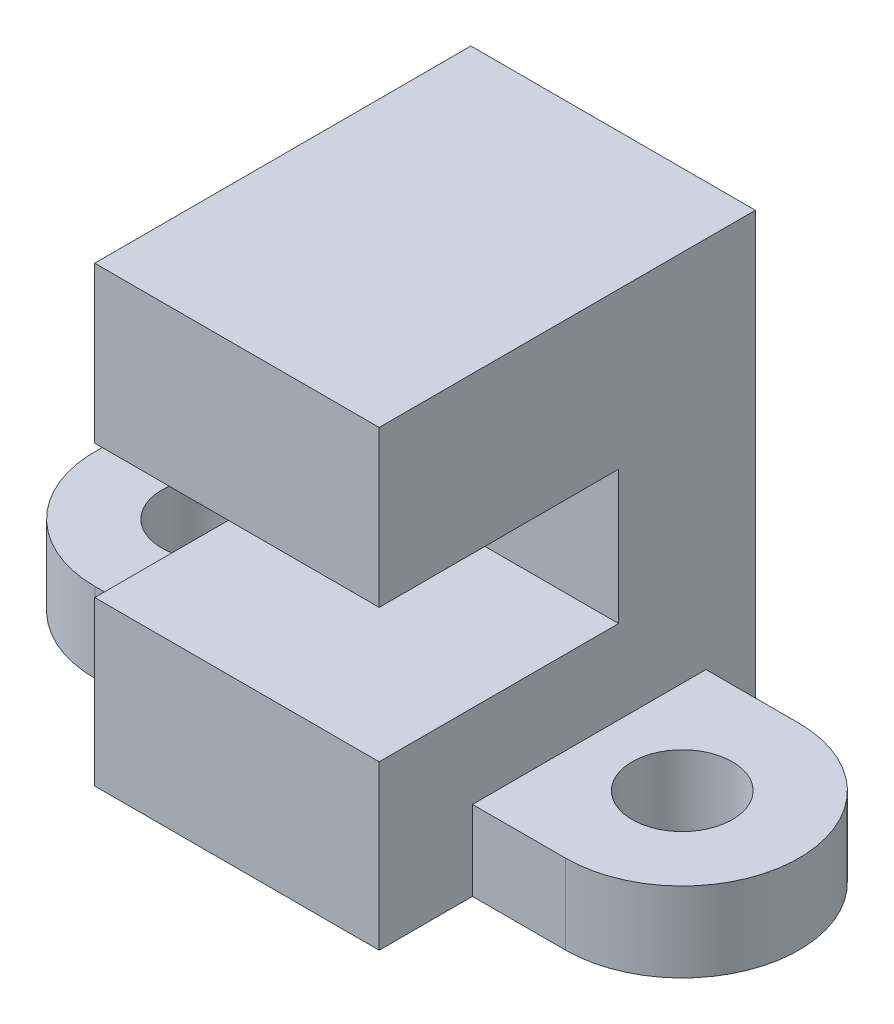
SolidWorks part; units mm, degrees
material "ABS"
ref_plane "Alzado" through (0, 0, 0) normal (0, 0, 1) x (1, 0, 0)
ref_plane "Planta" through (0, 0, 0) normal (0, 1, 0) x (1, 0, 0)
ref_plane "Vista lateral" through (0, 0, 0) normal (1, 0, 0) x (0, 0, -1)
sketch "Croquis1" plane through (0, 0, 0) normal (0, 0, 1) x (1, 0, 0)
  line L1 (-3.66, 5.825) -> (3.66, 5.825)
  line L2 (-3.66, 5.825) -> (-3.66, -5.825)
  line L3 (-3.66, -5.825) -> (3.66, -5.825)
  line L4 (3.66, 5.825) -> (3.66, -5.825)
  line L5 (-3.66, 5.825) -> (3.66, -5.825) construction
  line L6 (-3.66, -5.825) -> (3.66, 5.825) construction
  point P0 (0, 0)
  dimension "D1" = 11.65
  dimension "D2" = 7.32
extrude "Saliente-Extruir1" add sketch "Croquis1" along normal blind 3.52
sketch "Croquis2" plane through (0, 0, 3.52) normal (0, 0, 1) x (1, 0, 0)
  line L0 (3.66, -5.825) -> (3.66, 5.825) construction
  line L1 (-3.66, -5.825) -> (3.66, -5.825)
  line L2 (-3.66, -5.825) -> (-3.66, -1.625)
  line L3 (-3.66, -1.625) -> (3.66, -1.625)
  line L4 (3.66, -5.825) -> (3.66, -1.625)
  line L6 (-3.66, 5.825) -> (3.66, 5.825)
  line L7 (-3.66, 5.825) -> (-3.66, 1.815)
  line L8 (-3.66, 1.815) -> (3.66, 1.815)
  line L9 (3.66, 5.825) -> (3.66, 1.815)
  dimension "D1" = 4.2
  dimension "D2" = 4.01
extrude "Saliente-Extruir2" add sketch "Croquis2" along normal blind 6.16
sketch "Croquis3" plane through (0, -5.825, 0) normal (0, -1, 0) x (-1, 0, 0)
  line L0 (0, -9.68) -> (0, 0) construction
  line L1 (3.66, -9.68) -> (-3.66, -9.68) construction
  line L2 (-6.0536, -7.28) -> (-3.66, -7.28)
  line L3 (-3.66, -9.68) -> (-3.66, 0) construction
  line L4 (-6.0536, -1.27) -> (-3.66, -1.27)
  line L5 (6.0536, -1.27) -> (3.66, -1.27)
  line L6 (6.0536, -7.28) -> (3.66, -7.28)
  circle A0 centre (-6.0536, -4.275) radius 1.29
  arc A1 (-6.0536, -1.27) -> (-6.0536, -7.28) centre (-6.0536, -4.275) ccw
  circle A2 centre (6.0536, -4.275) radius 1.29
  arc A3 (6.0536, -1.27) -> (6.0536, -7.28) centre (6.0536, -4.275) cw
  line M5 (-3.66, 0) -> (-3.66, -9.68)
  line M7 (3.66, -9.68) -> (3.66, 0)
  dimension "D1" = 6.01
  dimension "D2" = 2.58
  dimension "D3" = 2.4
extrude "Saliente-Extruir3" add sketch "Croquis3" against normal blind 2.05 contours L4 A1 L2 A0 M5 | A3 L5 L6 A2 M7
